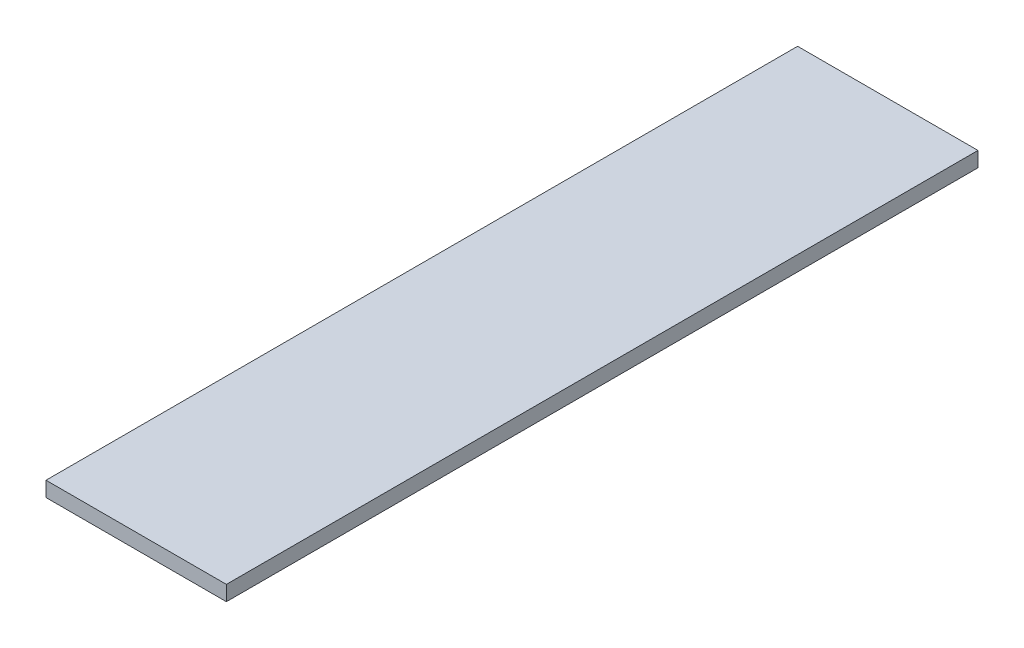
SolidWorks part; units mm, degrees
ref_plane "Ön Düzlem" through (0, 0, 0) normal (0, 0, 1) x (1, 0, 0)
ref_plane "Üst Düzlem" through (0, 0, 0) normal (0, 1, 0) x (1, 0, 0)
ref_plane "Sağ Düzlem" through (0, 0, 0) normal (1, 0, 0) x (0, 0, -1)
sketch "Sketch1" plane through (0, 0, 0) normal (0, 0, 1) x (1, 0, 0)
  line L12 (0, 0) -> (120, 0)
  line L13 (0, 0) -> (0, -10)
  line L14 (0, -10) -> (120, -10)
  line L15 (120, 0) -> (120, -10)
  dimension "D1" = 120
  dimension "D2" = 10
extrude "Boss-Extrude1" add sketch "Sketch1" along normal blind 500
